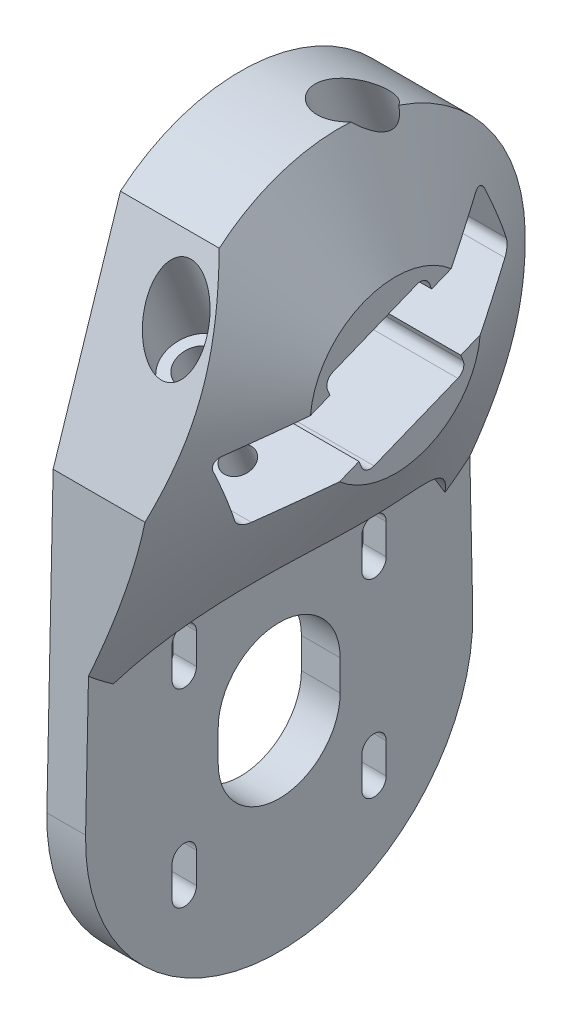
SolidWorks part; units mm, degrees
ref_plane "Front Plane" through (0, 0, 0) normal (0, 0, 1) x (1, 0, 0)
ref_plane "Top Plane" through (0, 0, 0) normal (0, 1, 0) x (1, 0, 0)
ref_plane "Right Plane" through (0, 0, 0) normal (1, 0, 0) x (0, 0, -1)
sketch "Sketch1" plane through (0, 0, 0) normal (1, 0, 0) x (0, 0, -1)
  line L0 (4.9732, 11.7161) -> (-11.7161, 4.9732)
  line L1 (4.9732, 11.7161) -> (11.7161, -4.9732)
  line L2 (-11.7161, 4.9732) -> (-4.9732, -11.7161)
  line L3 (11.7161, -4.9732) -> (-4.9732, -11.7161)
  line L4 (4.9732, 11.7161) -> (-4.9732, -11.7161) construction
  line L5 (-11.7161, 4.9732) -> (11.7161, -4.9732) construction
  line L6 (0, 0) -> (0, -57.15) construction
  line L7 (-30.4731, 0.6489) -> (-31.7428, -58.974)
  line L8 (31.7428, -58.974) -> (30.4731, 0.6489)
  line L9 (0, -57.15) -> (0, -103.9417) construction
  arc A0 (30.4731, 0.6489) -> (-30.4731, 0.6489) centre (0, 0) ccw
  arc A1 (-31.7428, -58.974) -> (31.7428, -58.974) centre (0, -59.65) ccw
  dimension "D1" = 2.5
  dimension "D2" = 30.48
  dimension "D6" = 57.15
  dimension "D7" = 31.75
  dimension "D8" = 0
  dimension "D3" = 18
  dimension "D4" = 18
  dimension "D5" = 22
extrude "Boss-Extrude1" add sketch "Sketch1" along normal blind 6.35
sketch "Sketch19" plane through (6.35, 0, 0) normal (1, 0, 0) x (0, 0, -1)
  line L0 (0, -59.65) -> (0, -54.65)
  line L1 (0, -54.65) -> (15.5563, -39.0937) construction
  line L2 (15.5563, -44.0937) -> (15.5563, -39.0937) construction
  line L3 (13.5563, -44.0937) -> (13.5563, -39.0937)
  line L4 (17.5563, -44.0937) -> (17.5563, -39.0937)
  line L5 (-10, -59.65) -> (-10, -54.65)
  line L6 (10, -59.65) -> (10, -54.65)
  line L7 (0, -57.15) -> (7.4061, -57.15) construction
  line L8 (15.5563, -44.0937) -> (0, -59.65) construction
  line L9 (17.5563, -70.2063) -> (17.5563, -75.2063)
  line L10 (13.5563, -70.2063) -> (13.5563, -75.2063)
  line L11 (-17.5563, -44.0937) -> (-17.5563, -39.0937)
  line L12 (-13.5563, -44.0937) -> (-13.5563, -39.0937)
  line L13 (-13.5563, -70.2063) -> (-13.5563, -75.2063)
  line L14 (-17.5563, -70.2063) -> (-17.5563, -75.2063)
  line L15 (-15.5563, -44.0937) -> (0, -59.65) construction
  line L16 (0, -59.65) -> (-15.5563, -75.2063) construction
  line L17 (0, -59.65) -> (15.5563, -75.2063) construction
  arc A0 (-31.7428, -58.974) -> (31.7428, -58.974) centre (0, -59.65) ccw construction
  arc A1 (-31.7428, -58.974) -> (31.7428, -58.974) centre (0, -59.65) ccw
  arc A2 (-10, -59.65) -> (10, -59.65) centre (0, -59.65) ccw
  arc A3 (17.5563, -75.2063) -> (13.5563, -75.2063) centre (15.5563, -75.2063) cw
  arc A4 (13.5563, -70.2063) -> (17.5563, -70.2063) centre (15.5563, -70.2063) cw
  arc A6 (17.5563, -39.0937) -> (13.5563, -39.0937) centre (15.5563, -39.0937) ccw
  arc A7 (13.5563, -44.0937) -> (17.5563, -44.0937) centre (15.5563, -44.0937) ccw
  arc A8 (-17.5563, -39.0937) -> (-13.5563, -39.0937) centre (-15.5563, -39.0937) cw
  arc A9 (10, -54.65) -> (-10, -54.65) centre (0, -54.65) ccw
  arc A10 (-13.5563, -44.0937) -> (-17.5563, -44.0937) centre (-15.5563, -44.0937) cw
  arc A11 (-13.5563, -70.2063) -> (-17.5563, -70.2063) centre (-15.5563, -70.2063) ccw
  arc A13 (-17.5563, -75.2063) -> (-13.5563, -75.2063) centre (-15.5563, -75.2063) ccw
  point P8 (0, -57.15)
  dimension "D1" = 135
  dimension "D3" = 22
  dimension "D5" = 4
  dimension "D6" = 5
  dimension "D4" = 4
  dimension "D8" = 0
  dimension "D2" = 5
  dimension "D7" = 45
extrude "Cut-Extrude18" cut sketch "Sketch19" against normal blind 10
sketch "Sketch20" plane through (6.35, 0, 0) normal (1, 0, 0) x (0, 0, -1)
  circle A0 centre (0, 0) radius 57.15
  arc A1 (-31.7428, -58.974) -> (31.7428, -58.974) centre (0, -59.65) ccw construction
  point P3 (0, -91.4)
extrude "Boss-Extrude5" add sketch "Sketch20" along normal blind 19.05
sketch "Sketch21" plane through (0, 0, 0) normal (-1, 0, 0) x (0, 0, 1)
  line L0 (-24.6312, 3.1029) -> (-10.7234, -2.5162)
  line L1 (11.7161, 4.9732) -> (4.9732, -11.7161) construction
  line L2 (3.3715, 8.3447) -> (-3.3715, -8.3447) construction
  line L3 (-4.9732, 11.7161) -> (-11.7161, -4.9732) construction
  line L4 (-4.9732, 11.7161) -> (11.7161, 4.9732) construction
  line L5 (11.7161, 4.9732) -> (10.7234, 2.5162)
  line L6 (-11.7161, -4.9732) -> (4.9732, -11.7161) construction
  line L7 (-4.9732, 11.7161) -> (-5.9659, 9.2591)
  line L8 (-4.9732, 11.7161) -> (11.7161, 4.9732)
  line L9 (-22.2524, 8.9906) -> (-14.2742, 5.7671) construction
  line L10 (19.8737, -14.8782) -> (5.9659, -9.2591)
  line L11 (19.8737, -14.8782) -> (24.6312, -3.1029)
  line L12 (-24.6312, 3.1029) -> (-19.8737, 14.8782)
  line L13 (24.6312, -3.1029) -> (10.7234, 2.5162)
  line L14 (-11.7161, -4.9732) -> (4.9732, -11.7161)
  line L16 (4.9732, -11.7161) -> (5.9659, -9.2591)
  line L17 (-11.7161, -4.9732) -> (-10.7234, -2.5162)
  line L18 (11.7161, 4.9732) -> (-4.9732, 11.7161)
  line L21 (-10.7234, -2.5162) -> (-11.7161, -4.9732)
  line L24 (-10.7234, -2.5162) -> (-24.6312, 3.1029)
  line L27 (-5.9659, 9.2591) -> (-4.9732, 11.7161)
  line L29 (-5.9659, 9.2591) -> (-19.8737, 14.8782)
  line L30 (5.9659, -9.2591) -> (4.9732, -11.7161)
  line L31 (10.7234, 2.5162) -> (11.7161, 4.9732)
  point P4 (-22.2524, 8.9906)
  line M13 (-11.7161, -4.9732) -> (-4.9732, 11.7161)
  line M14 (-4.9732, 11.7161) -> (11.7161, 4.9732)
  line M15 (11.7161, 4.9732) -> (4.9732, -11.7161)
  line M16 (4.9732, -11.7161) -> (-11.7161, -4.9732)
  dimension "D1" = 15
  dimension "D2" = 12.7
  dimension "D3" = 15
extrude "Cut-Extrude14" cut sketch "Sketch21" against normal through all contours L29 L12 L0 M13 | M13 M16 M15 M14 | L11 L13 L10 M15
sketch "Sketch22" plane through (0, 5.8876, 2.3788) normal (0, -0.9272, -0.3746) x (1, 0, 0)
  line L0 (25.4, 9) -> (0, 9) construction
  line L2 (0, 28.0111) -> (0, -30.48) construction
  circle A0 centre (12.5, 16.5) radius 3.175
  dimension "D2" = 12.5
  dimension "D3" = 6.35
  dimension "D1" = 7.5
extrude "Cut-Extrude15" cut sketch "Sketch22" against normal through all
ref_plane "Plane1" through (0, 10.5977, 4.2818) normal (0, -0.9272, -0.3746) x (1, 0, 0)
sketch "Sketch24" plane through (0, 10.5977, 4.2818) normal (0, -0.9272, -0.3746) x (1, 0, 0)
  circle A0 centre (12.5, 16.5) radius 5
  dimension "D1" = 10
extrude "Cut-Extrude16" cut sketch "Sketch24" against normal through all
sketch "Sketch25" plane through (0, -5.8876, -2.3788) normal (0, 0.9272, 0.3746) x (-1, 0, 0)
  circle A0 centre (-12.5, 16.5) radius 3.175 construction
  circle A1 centre (-12.5, 16.5) radius 3.175
  circle A2 centre (-12.5, 16.5) radius 2.3813
  dimension "D1" = 0.7937
extrude "Cut-Extrude17" cut sketch "Sketch25" against normal blind 10 contours A2
ref_plane "Plane2" through (0, 0, 0) normal (0, 0.3746, -0.9272) x (-1, 0, 0)
mirror "Mirror1" about plane through (0, 0, 0) normal (0, 0.3746, -0.9272) of "Cut-Extrude17", "Cut-Extrude15", "Cut-Extrude16"
mirror "Mirror2" about plane through (0, 0, 0) normal (1, 0, 0) of bodies 124 126
delete or keep bodies "Body-Delete/Keep 1" type delete bodies bodies 127
chamfer "Chamfer2" distance 2.5 angle 45 8 edges at (0, -46.0937, 15.5563) (0, -41.5937, 13.5563) (0, -37.0937, 15.5563) (0, -41.5937, 17.5563) (0, -46.0937, -15.5563) (0, -41.5937, -17.5563) (0, -41.5937, -13.5563) (0, -37.0937, -15.5563)
sketch "Sketch26" plane through (0, 0, 0) normal (-1, 0, 0) x (0, 0, 1)
  line L0 (11.4538, -58.2291) -> (27.0119, -8.4408)
  line L1 (0, 0) -> (0, -54.65) construction
  circle A0 centre (0, -54.65) radius 12
  circle A1 centre (0, 0) radius 28.3
  dimension "D1" = 24
  dimension "D2" = 56.6
fillet "Fillet1" radius 1.5875 8 edges at (12.7, 3.1029, -24.6312) (12.7, 14.8782, -19.8737) (12.7, -3.1029, 24.6312) (12.7, -14.8782, 19.8737) (12.7, 11.7161, -4.9732) (12.7, 4.9732, 11.7161) (12.7, -11.7161, 4.9732) (12.7, -4.9732, -11.7161)
sketch "Sketch28" plane through (6.35, 0, 0) normal (1, 0, 0) x (0, 0, -1)
  arc A0 (-10, -54.65) -> (10, -54.65) centre (0, -54.65) ccw construction
  arc A1 (-10, -54.65) -> (10, -54.65) centre (0, -54.65) ccw
  circle A3 centre (0, -54.65) radius 31
  dimension "D1" = 62
extrude "Cut-Extrude19" cut sketch "Sketch28" along normal through all contours A3
sketch "Sketch29" plane through (25.4, 0, 0) normal (1, 0, 0) x (0, 0, -1)
  arc A1 (30.4731, 0.6489) -> (-30.4731, 0.6489) centre (0, 0) ccw construction
  arc A2 (30.4731, 0.6489) -> (-30.4731, 0.6489) centre (0, 0) ccw
  circle A3 centre (0, 0) radius 13.97
sketch "Sketch30" plane through (6.35, 0, 0) normal (1, 0, 0) x (0, 0, -1)
  circle A0 centre (0, 0) radius 57.15
sketch "Sketch31" plane through (0, 0, 0) normal (0, 1, 0) x (1, 0, 0)
  line L1 (25.4, -13.97) -> (25.4, 14.03)
  line L3 (6.35, -48.173) -> (4.8643, 48.1615)
  line L4 (25.4, -13.97) -> (6.35, -48.173)
  line L5 (6.35, -48.173) -> (6.35, -58.97)
  line L6 (6.35, -58.97) -> (25.4, -58.97)
  line L7 (25.4, -58.97) -> (25.4, -13.97)
  line L8 (25.4, 0) -> (0, 0) construction
  dimension "D1" = 45
  dimension "D2" = 30
  dimension "D3" = 28
  dimension "D4" = 28
revolve "Cut-Revolve1" cut sketch "Sketch31" angle 360 about L8
sketch "Sketch32" plane through (6.35, 0, 0) normal (-1, 0, 0) x (0, 0, 1)
  line L0 (30.4731, 0.6489) -> (31.7428, -58.974) construction
  line L1 (-31.7428, -58.974) -> (-30.4731, 0.6489) construction
  line L2 (30.4731, 0.6489) -> (31.7428, -58.974)
  line L3 (-31.7428, -58.974) -> (-30.4731, 0.6489)
  arc A0 (30.4731, 0.6489) -> (-30.4731, 0.6489) centre (0, 0) ccw construction
  arc A1 (30.4731, 0.6489) -> (-30.4731, 0.6489) centre (0, 0) ccw
  circle A2 centre (0, 0) radius 57.15 construction
  circle A3 centre (0, 0) radius 57.15
  arc M2 (31.2673, -36.6468) -> (-31.2673, -36.6468) centre (0, 0) ccw
  line M3 (-31.2673, -36.6468) -> (-30.4731, 0.6489)
  arc M4 (-30.4731, 0.6489) -> (30.4731, 0.6489) centre (0, 0) cw
  line M5 (30.4731, 0.6489) -> (31.2673, -36.6468)
extrude "Cut-Extrude20" cut sketch "Sketch32" against normal through all contours M5 M2 M3 M4
sketch "Sketch33" plane through (0, 0, 0) normal (-1, 0, 0) x (0, 0, 1)
  line L0 (30.4731, 0.6489) -> (31.7428, -58.974) construction
  line L1 (30.4731, 0.6489) -> (31.7428, -58.974)
  line L2 (30.7146, -10.6896) -> (19.6783, 23.2765)
  line L3 (23.1593, -2.5083) -> (10.7234, 2.5162) construction
  arc A0 (30.4731, 0.6489) -> (-30.4731, 0.6489) centre (0, 0) ccw construction
  arc A1 (30.4731, 0.6489) -> (-30.4731, 0.6489) centre (0, 0) ccw
  arc M35 (30.4731, 0.6489) -> (-30.4731, 0.6489) centre (0, 0) ccw
  dimension "D1" = 50
  dimension "D2" = 25.908
extrude "Cut-Extrude21" cut sketch "Sketch33" against normal through all contours L2 L1 M35
sketch "Sketch34" plane through (25.4, 0, 0) normal (1, 0, 0) x (0, 0, -1)
  line L0 (-9.1586, -10.549) -> (-18.4018, -14.2835) construction
  line L1 (-9.1586, -10.549) -> (-18.4018, -14.2835)
  arc A0 (-9.1586, -10.549) -> (13.9161, -1.2262) centre (0, 0) ccw construction
  dimension "D1" = 23.2947
sketch "Sketch35" plane through (0, -5.8876, -2.3788) normal (0, 0.9272, 0.3746) x (-1, 0, 0)
  line L0 (0, 22.4125) -> (0, 9) construction
  line L4 (-19.553, 24) -> (0, 24) construction
  line L5 (-19.553, 24) -> (0, 24)
  spline S0 degree 3 poles (-713.6017, 742.9697) (105.8121, 182.6367) (25.0413, 108.9315) (-55.3928, -44.7506) (-73.6374, -114.0098) (766.847, -597.7234) knots -27.053447 -27.053447 -27.053447 -27.053447 0.5 0.5 19.2326 19.2326 19.2326 19.2326 only from (-20.2064, 22.4125) to (-25.4, 12.4434) construction
  spline S1 degree 3 poles (-20.2064, 22.4125) (-21.0914, 20.7611) (-21.9711, 19.1068) (-23.7089, 15.7865) (-24.5676, 14.1214) (-25.4, 12.4434) knots 0 0 0 0 0.5 0.5 1 1 1 1
  dimension "D1" = 5.1936
  dimension "D2" = 20.2064
  dimension "D3" = 19.553
equation "\".75i\"=14.27"
